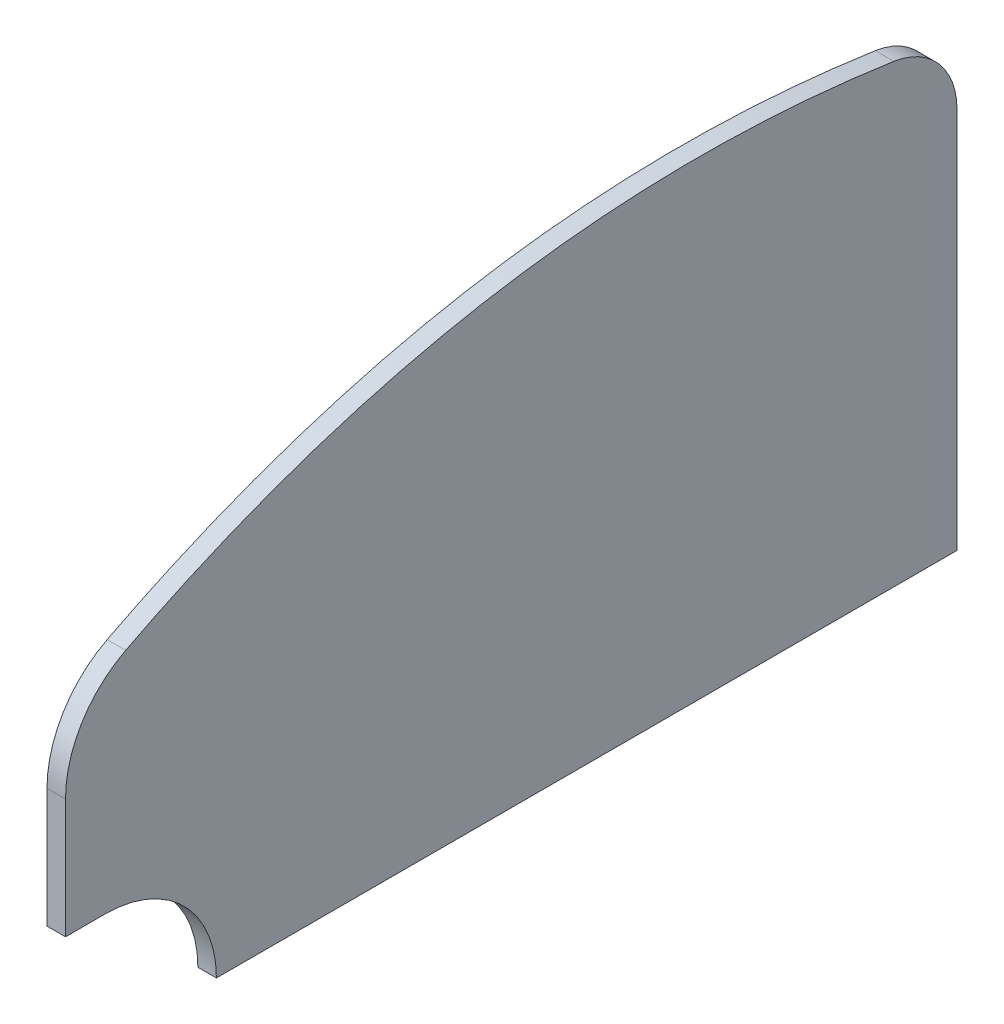
SolidWorks part; units mm, degrees
ref_plane "Front Plane" through (0, 0, 0) normal (0, 0, 1) x (1, 0, 0)
ref_plane "Top Plane" through (0, 0, 0) normal (0, 1, 0) x (1, 0, 0)
ref_plane "Right Plane" through (0, 0, 0) normal (1, 0, 0) x (0, 0, -1)
sketch "Sketch1" plane through (0, 0, 0) normal (1, 0, 0) x (0, 0, -1)
  line L0 (-59.3103, 100.9655) -> (-59.3103, -26.0345)
  line L1 (-59.3103, -26.0345) -> (-31.9898, -26.0345)
  line L2 (44.2102, -102.2345) -> (552.2102, -102.2345)
  line L3 (552.2102, -102.2345) -> (552.2102, 202.5655)
  arc A0 (-31.9898, -26.0345) -> (44.2102, -102.2345) centre (-31.9898, -102.2345) cw
  spline S0 degree 2 poles (552.2102, 202.5655) (225.1412, 265.7021) (-59.3103, 100.9655) knots 0 0 0 1 1 1
  dimension "D1" = 304.8
  dimension "D2" = 508
extrude "Boss-Extrude1" add sketch "Sketch1" along normal blind 12.7 contours L0 L1 A0 L2 L3 S0
fillet "Fillet1" radius 76.2 1 edges at (6.35, 100.9655, 59.3103)
fillet "Fillet2" radius 50.8 1 edges at (6.35, 202.5655, -552.2102)
